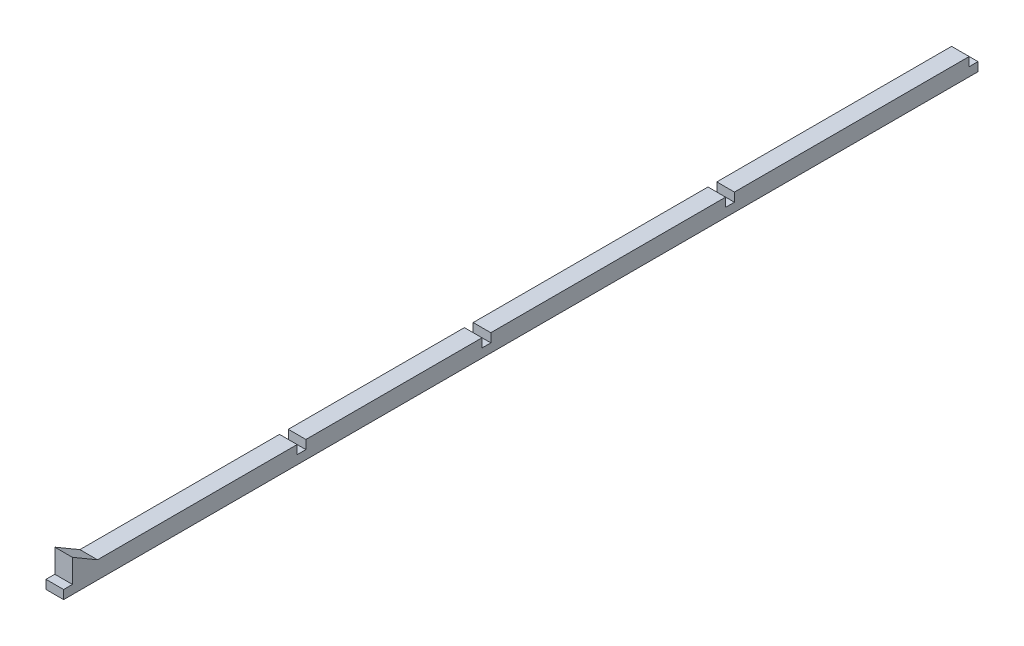
SolidWorks part; units mm, degrees
ref_plane "Спереди" through (0, 0, 0) normal (0, 0, 1) x (1, 0, 0)
ref_plane "Сверху" through (0, 0, 0) normal (0, 1, 0) x (1, 0, 0)
ref_plane "Справа" through (0, 0, 0) normal (1, 0, 0) x (0, 0, -1)
other "Configuration Table"
sketch "Эскиз1" plane through (0, 0, 0) normal (1, 0, 0) x (0, 0, -1)
  line L0 (-411.8084, 0) -> (-100.2484, 0)
  line L2 (-400.2594, 6) -> (-332.2484, 6)
  line L3 (-411.8084, 0) -> (-411.8084, 3)
  line L4 (-411.8084, 3) -> (-408.8084, 3)
  line L5 (-408.8084, 3) -> (-408.8084, 6)
  line L6 (-408.8084, 11) -> (-400.2594, 6)
  line L9 (-332.2484, 6) -> (-332.2484, 3)
  line L10 (-332.2484, 3) -> (-329.2484, 3)
  line L11 (-329.2484, 3) -> (-329.2484, 6)
  line L12 (-269.2484, 6) -> (-269.2484, 3)
  line L13 (-269.2484, 3) -> (-266.2484, 3)
  line L14 (-266.2484, 3) -> (-266.2484, 6)
  line L15 (-186.2484, 6) -> (-186.2484, 3)
  line L16 (-186.2484, 3) -> (-183.2484, 3)
  line L17 (-183.2484, 3) -> (-183.2484, 6)
  line L18 (-103.2484, 6) -> (-103.2484, 3)
  line L19 (-103.2484, 3) -> (-100.2484, 3)
  line L27 (-329.2484, 6) -> (-269.2484, 6)
  line L28 (-266.2484, 6) -> (-186.2484, 6)
  line L29 (-183.2484, 6) -> (-103.2484, 6)
  line L57 (-408.8084, 11) -> (-408.8084, 6)
  line L63 (-100.2484, 3) -> (-100.2484, 0)
  point P6 (-400.2594, 6)
  dimension "D3" = 5
  dimension "D4" = 3
  dimension "D5" = 3
  dimension "D6" = 3
  dimension "D7" = 6
  dimension "D9" = 3
  dimension "D10" = 76.56
  dimension "D11" = 3
  dimension "D12" = 3
  dimension "D13" = 3
  dimension "D16" = 60
  dimension "D17" = 80
  dimension "D20" = 80
extrude "Бобышка-Вытянуть1" add sketch "Эскиз1" along normal blind 6
